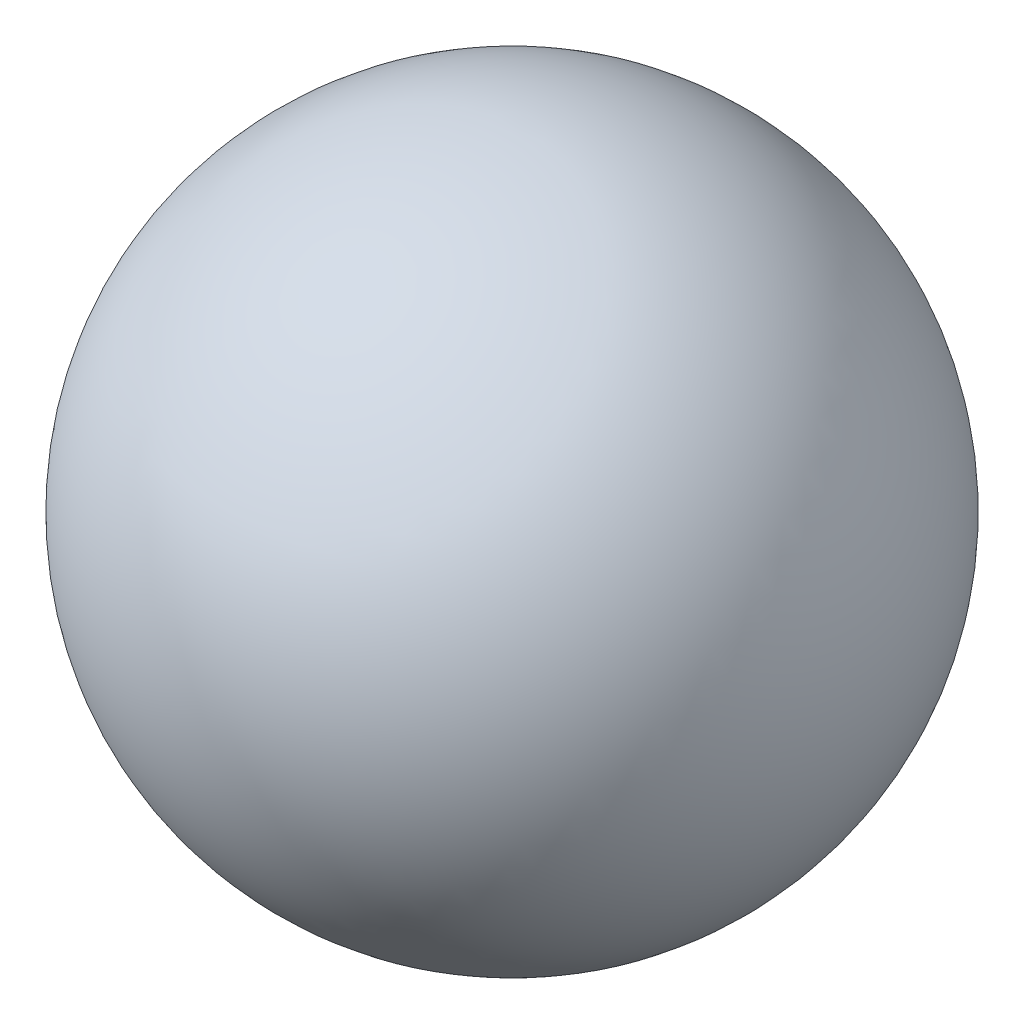
SolidWorks part; units mm, degrees
ref_plane "Front Plane" through (0, 0, 0) normal (0, 0, 1) x (1, 0, 0)
ref_plane "Top Plane" through (0, 0, 0) normal (0, 1, 0) x (1, 0, 0)
ref_plane "Right Plane" through (0, 0, 0) normal (1, 0, 0) x (0, 0, -1)
sketch "Sketch1" plane through (0, 0, 0) normal (0, 0, 1) x (1, 0, 0)
  line L0 (0, 0) -> (0, -50000) construction
  line L1 (0, 31.25) -> (0, -31.25)
  arc A0 (0, -31.25) -> (0, 31.25) centre (0, 0) ccw
  dimension "D1" = 62.5
revolve "Revolve2" add sketch "Sketch1" angle 360 about L0
